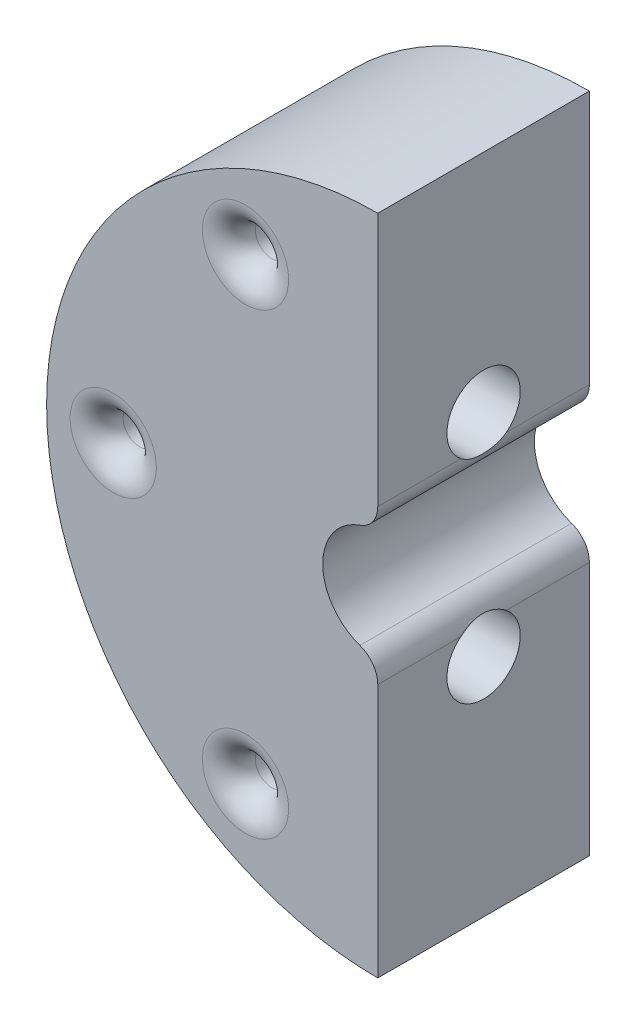
SolidWorks part; units mm, degrees
material "PBT General Purpose"
ref_plane "Front" through (0, 0, 0) normal (0, 0, 1) x (1, 0, 0)
ref_plane "Top" through (0, 0, 0) normal (0, 1, 0) x (1, 0, 0)
ref_plane "Right" through (0, 0, 0) normal (1, 0, 0) x (0, 0, -1)
sketch "Sketch1" plane through (0, 0, 0) normal (0, 0, 1) x (1, 0, 0)
  line L0 (-7.9375, 0) -> (0, 0) construction
  line L1 (-7.9375, 0) -> (-9.9375, 0) construction
  line L2 (-3.9687, 6.8741) -> (0, 0) construction
  circle A0 centre (0, 0) radius 1.651
  circle A1 centre (0, 0) radius 9.9375
  circle A2 centre (-7.9375, 0) radius 0.5
  circle A3 centre (-3.9687, 6.8741) radius 0.5
  circle A4 centre (3.9688, 6.8741) radius 0.5
  circle A5 centre (7.9375, 0) radius 0.5
  circle A6 centre (3.9688, -6.8741) radius 0.5
  circle A7 centre (-3.9688, -6.8741) radius 0.5
  dimension "D1" = 3.302
  dimension "D2" = 7.9375
  dimension "D3" = 1
  dimension "D4" = 2
  dimension "D6" = 60
  dimension "D5" = 6
extrude "Boss-Extrude1" add sketch "Sketch1" along normal blind 6.35
sketch "Sketch2" plane through (0, 0, 6.35) normal (0, 0, 1) x (1, 0, 0)
  line L0 (0, 0) -> (0, 25.4)
  line L1 (0, 25.4) -> (50.8, 25.4)
  line L2 (50.8, 25.4) -> (50.8, -25.4)
  line L3 (50.8, -25.4) -> (0, -25.4)
  line L4 (0, -25.4) -> (0, 0)
  dimension "D1" = 50.8
  dimension "D2" = 50.8
extrude "Cut-Extrude1" cut sketch "Sketch2" against normal through all
fillet "Fillet1" radius 0.7937 2 edges at (0, 1.651, 3.175) (0, -1.651, 3.175)
fillet "Fillet2" radius 0.7937 6 edges at (-3.4687, 6.8741, 0) (-3.4687, 6.8741, 6.35) (-3.4688, -6.8741, 0) (-3.4688, -6.8741, 6.35) (-7.4375, 0, 0) (-7.4375, 0, 6.35)
ref_plane "Plane1" through (-9.9375, 0, 0) normal (-1, 0, 0) x (0, 0, 1)
hole_wizard "CBORE for M2 SHCS1" positions "Sketch9" profile "Sketch8" counterbore size "M2" standard "Ansi Metric" end condition through all
sketch "Sketch9" plane through (-9.9375, 0, 0) normal (-1, 0, 0) x (0, 0, 1)
  line L0 (0, 0) -> (6.35, 0) construction
  line L1 (0, 9.9375) -> (0, -9.9375) construction
  line L2 (6.35, -9.9375) -> (6.35, 9.9375) construction
  line L4 (3.175, 3.175) -> (3.175, 0) construction
  line L5 (3.175, 0) -> (3.175, -3.175) construction
  point P1 (3.175, 3.175)
  point P3 (3.175, -3.175)
  dimension "D1" = 6.35
sketch "Sketch8" plane through (-9.9375, 3.175, 3.175) normal (0, 1, 0) x (0, 0, 1)
  line L0 (0, 0) -> (0, 9.9375)
  line L1 (0, 9.9375) -> (1.1, 9.9375)
  line L3 (1.1, 9.9375) -> (1.1, 5.175)
  line L4 (1.1, 5.175) -> (2.2, 5.175)
  line L5 (2.2, 5.175) -> (2.2, 0)
  line L7 (2.2, 0) -> (0, 0)
  line L11 (0, -6.35) -> (0, 107.95) construction
  dimension "Thru Hole Dia." = 2.2
  dimension "Thru Hole Depth" = 9.9375
  dimension "C'Bore Dia." = 4.4
  dimension "C'Bore Depth" = 5.175
